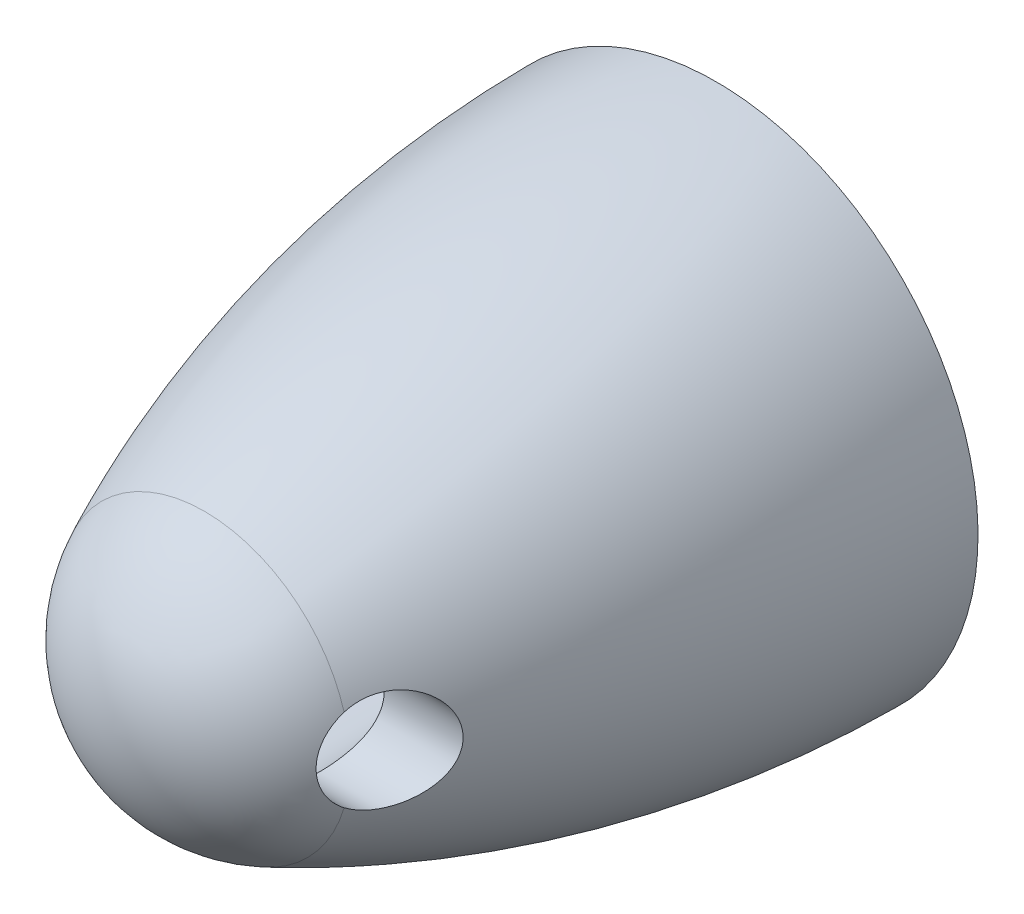
SolidWorks part; units mm, degrees
material "6061-T6 (SS)"
ref_plane "Front Plane" through (0, 0, 0) normal (0, 0, 1) x (1, 0, 0)
ref_plane "Top Plane" through (0, 0, 0) normal (0, 1, 0) x (1, 0, 0)
ref_plane "Right Plane" through (0, 0, 0) normal (1, 0, 0) x (0, 0, -1)
sketch "Sketch1" plane through (0, 0, 0) normal (1, 0, 0) x (0, 0, -1)
  line L0 (0, 0) -> (-52.938, 0) construction
  line L1 (0, 0) -> (0, 6.5)
  line L2 (0, 6.5) -> (0.1243, 6.5)
  line L3 (-15, 0) -> (0, 0)
  arc A0 (0.1243, 6.5) -> (-12.7114, 3.6154) centre (0.1243, -23.5) ccw
  arc A1 (-12.7114, 3.6154) -> (-15, 0) centre (-11, 0) ccw
  dimension "D1" = 30
  dimension "D2" = 13
  dimension "D3" = 4
  dimension "D4" = 15
revolve "Revolve1" add sketch "Sketch1" angle 360 about L0
hole_wizard "M6x1.0 Tapped Hole1" positions "Sketch3" profile "Sketch2" tap size "M6x1.0" standard "Ansi Metric"
sketch "Sketch3" plane through (0, 0, 0) normal (0, 0, -1) x (-1, 0, 0)
  point P0 (0, 0)
sketch "Sketch2" plane through (0, 0, 0) normal (1, 0, 0) x (0, 1, 0)
  line L0 (0, 0) -> (0, 14.5019)
  line L1 (0, 14.5019) -> (2.5, 12.9997)
  line L2 (2.5, 12.9997) -> (2.5, 0)
  line L5 (2.5, 0) -> (0, 0)
  line L10 (0, 14.5019) -> (-2.5, 12.9997) construction
  line L11 (0, -6.35) -> (0, 107.95) construction
  dimension "Tap Drill Dia." = 5
  dimension "Tap Drill Depth" = 12.9997
  dimension "Drill Angle" = 118
sketch "Sketch4" plane through (0, 0, 0) normal (1, 0, 0) x (0, 0, -1)
  line L0 (0, -6.4997) -> (0, 6.4997) construction
  circle A0 centre (-12, 0) radius 1.25
  dimension "D2" = 2.5
  dimension "D1" = 12
extrude "Cut-Extrude1" cut sketch "Sketch4" against normal mid plane 25.4
